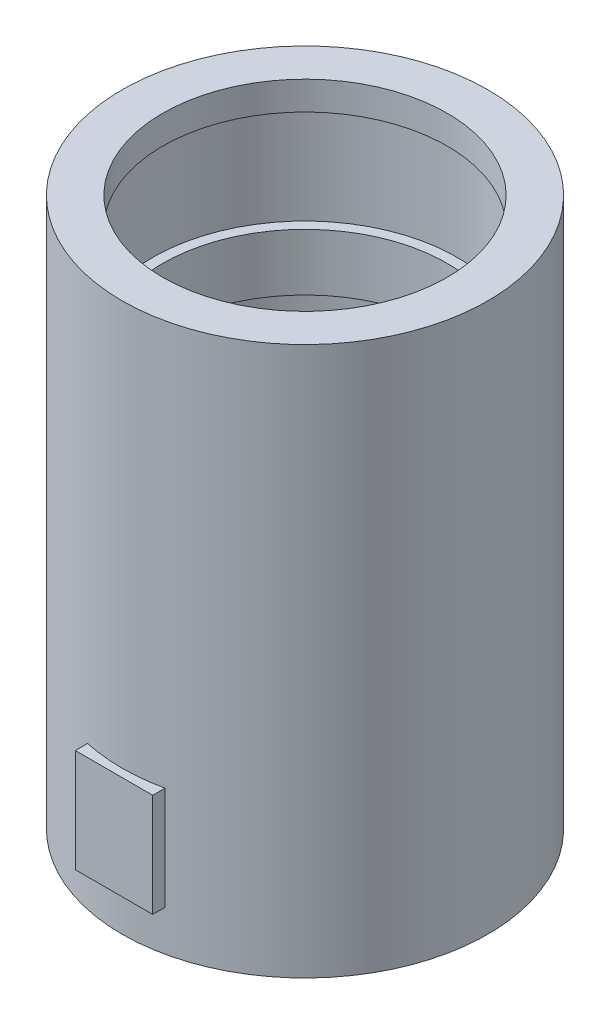
SolidWorks part; units mm, degrees
material "ABS"
ref_plane "Front" through (0, 0, 0) normal (0, 0, 1) x (1, 0, 0)
ref_plane "Top" through (0, 0, 0) normal (0, 1, 0) x (1, 0, 0)
ref_plane "Right" through (0, 0, 0) normal (1, 0, 0) x (0, 0, -1)
sketch "Sketch1" plane through (0, 0, 0) normal (0, 1, 0) x (1, 0, 0)
  circle A0 centre (0, 0) radius 45
  dimension "D1" = 90
extrude "Boss-Extrude1" add sketch "Sketch1" along normal blind 135
sketch "Sketch2" plane through (0, 135, 0) normal (0, 1, 0) x (1, 0, 0)
  circle A0 centre (0, 0) radius 35
  dimension "D1" = 70
extrude "Cut-Extrude1" cut sketch "Sketch2" against normal blind 90
ref_plane "Plane1" through (0, 128, 0) normal (0, 1, 0) x (1, 0, 0)
ref_plane "Plane2" through (0, 89, 0) normal (0, 1, 0) x (1, 0, 0)
sketch "Sketch3" plane through (0, 128, 0) normal (0, 1, 0) x (1, 0, 0)
  circle A0 centre (0, 0) radius 35
  circle A1 centre (0, 0) radius 37.5
  dimension "D1" = 70
  dimension "D2" = 75
extrude "Cut-Extrude2" cut sketch "Sketch3" against normal blind 25
sketch "Sketch4" plane through (0, 89, 0) normal (0, 1, 0) x (1, 0, 0)
  circle A0 centre (0, 0) radius 35
  circle A1 centre (0, 0) radius 37.5
  dimension "D1" = 70
  dimension "D2" = 75
extrude "Cut-Extrude3" cut sketch "Sketch4" against normal blind 25
sketch "Sketch5" plane through (0, 45, 0) normal (0, 1, 0) x (1, 0, 0)
  circle A0 centre (0, 0) radius 7.5
  dimension "D1" = 15
extrude "Cut-Extrude4" cut sketch "Sketch5" against normal blind 5
ref_plane "Plane3" through (0, 0, 45) normal (0, 0, 1) x (1, 0, 0)
sketch "Sketch6" plane through (0, 0, 45) normal (0, 0, 1) x (1, 0, 0)
  line L1 (-9.525, 35.4) -> (9.525, 35.4)
  line L2 (-9.525, 35.4) -> (-9.525, 10)
  line L3 (-9.525, 10) -> (9.525, 10)
  line L4 (9.525, 35.4) -> (9.525, 10)
  line L5 (9.525, 29.9042) -> (45, 29.9042) construction
  line L6 (45, 0) -> (45, 135) construction
  line L7 (-9.525, 29.9042) -> (-45, 29.9042) construction
  line L9 (-45, 135) -> (-45, 0) construction
  line L10 (50, 0) -> (-50, 0) construction
  dimension "D1" = 25.4
  dimension "D2" = 19.05
  dimension "D3" = 10
extrude "Boss-Extrude2" add sketch "Sketch6" along normal blind 2 and the other way blind 4
